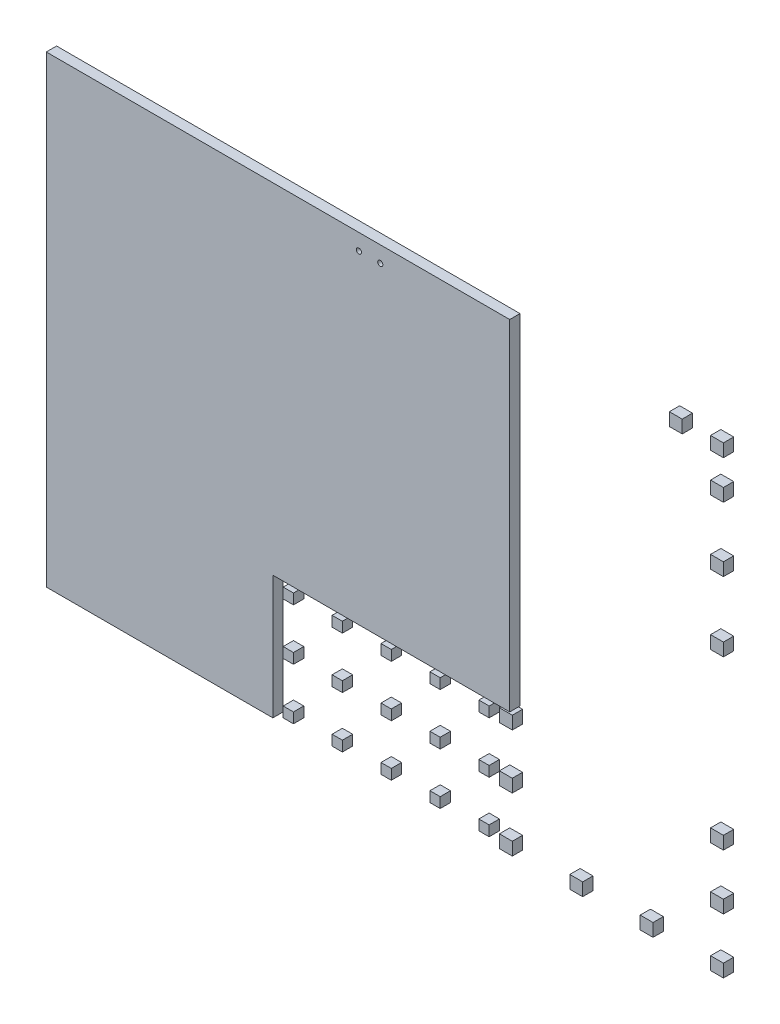
SolidWorks part; units mm, degrees
ref_plane "Спереди" through (0, 0, 0) normal (0, 0, 1) x (1, 0, 0)
ref_plane "Сверху" through (0, 0, 0) normal (0, 1, 0) x (1, 0, 0)
ref_plane "Справа" through (0, 0, 0) normal (1, 0, 0) x (0, 0, -1)
sketch "Эскиз1" plane through (0, 0, 0) normal (0, 0, 1) x (1, 0, 0)
  line L0 (0, 0) -> (9000, 0)
  line L1 (9000, 0) -> (9000, -6600)
  line L2 (9000, -6600) -> (4400, -6600)
  line L3 (4400, -6600) -> (4400, -9000)
  line L4 (4400, -9000) -> (0, -9000)
  line L5 (0, -9000) -> (0, 0)
  line L6 (8800, -4500) -> (8800, -9000) construction
  line L7 (8800, -9000) -> (9050, -9000)
  line L8 (8800, -9000) -> (8800, -8750)
  line L9 (8800, -8750) -> (9050, -8750)
  line L14 (9050, -9000) -> (9050, -8750)
  line L15 (9000, -203) -> (9000, -6400) construction
  line L16 (8797, -6600) -> (4400, -6600) construction
  line L17 (4400, -8797) -> (4400, -6603) construction
  line L18 (203, -9000) -> (4200, -9000) construction
  line L19 (8800, -6630) -> (9050, -6630)
  line L20 (8800, -6630) -> (8800, -6880)
  line L21 (8800, -6880) -> (9050, -6880)
  line L22 (9050, -6630) -> (9050, -6880)
  line L23 (9050, -6880) -> (9050, -7690) construction
  line L24 (8800, -7690) -> (9050, -7690)
  line L25 (8800, -7690) -> (8800, -7940)
  line L26 (8800, -7940) -> (9050, -7940)
  line L27 (9050, -7690) -> (9050, -7940)
  line L28 (9050, -7940) -> (9050, -8750) construction
  line L29 (13150, -9000) -> (0, -9000) construction
  line L30 (10166.6667, -8750) -> (10416.6667, -8750)
  line L31 (10166.6667, -8750) -> (10166.6667, -9000)
  line L32 (10166.6667, -9000) -> (10416.6667, -9000)
  line L33 (10416.6667, -8750) -> (10416.6667, -9000)
  line L34 (9050, -8750) -> (10166.6667, -8750) construction
  line L35 (11533.3333, -8750) -> (11783.3333, -8750)
  line L36 (11533.3333, -8750) -> (11533.3333, -9000)
  line L37 (11533.3333, -9000) -> (11783.3333, -9000)
  line L38 (11783.3333, -8750) -> (11783.3333, -9000)
  line L43 (12900, -8750) -> (13150, -8750)
  line L44 (12900, -8750) -> (12900, -9000)
  line L45 (12900, -9000) -> (13150, -9000)
  line L46 (13150, -8750) -> (13150, -9000)
  line L47 (10416.6667, -8750) -> (11533.3333, -8750) construction
  line L48 (11783.3333, -8750) -> (12900, -8750) construction
  line L49 (13150, -4500) -> (13150, -9000) construction
  line L50 (13150, -6600) -> (12900, -6600)
  line L51 (13150, -6600) -> (13150, -6850)
  line L52 (13150, -6850) -> (12900, -6850)
  line L53 (12900, -6600) -> (12900, -6850)
  line L54 (13150, -7675) -> (12900, -7675)
  line L55 (13150, -7675) -> (13150, -7925)
  line L56 (13150, -7925) -> (12900, -7925)
  line L57 (12900, -7675) -> (12900, -7925)
  line L58 (12900, -7675) -> (12900, -6850) construction
  line L59 (13150, -3600) -> (12900, -3600)
  line L60 (13150, -3600) -> (13150, -3350)
  line L61 (13150, -3350) -> (12900, -3350)
  line L62 (12900, -3600) -> (12900, -3350)
  line L63 (13150, -2000) -> (12900, -2000)
  line L64 (13150, -2000) -> (13150, -2250)
  line L65 (13150, -2250) -> (12900, -2250)
  line L66 (12900, -2000) -> (12900, -2250)
  line L67 (13150, -1000) -> (12900, -1000)
  line L68 (13150, -1000) -> (13150, -750)
  line L69 (13150, -750) -> (12900, -750)
  line L70 (12900, -1000) -> (12900, -750)
  line L71 (13150, 0) -> (12900, 0)
  line L72 (13150, 0) -> (13150, -250)
  line L73 (13150, -250) -> (12900, -250)
  line L74 (12900, 0) -> (12900, -250)
  line L75 (12100, 0) -> (12350, 0)
  line L76 (12100, 0) -> (12100, -250)
  line L77 (12100, -250) -> (12350, -250)
  line L78 (12350, 0) -> (12350, -250)
  line L79 (12900, -7925) -> (12900, -8750) construction
  line L80 (4800, -6900) -> (4800, -7700) construction
  line L81 (4600, -6700) -> (4800, -6700)
  line L82 (4600, -6700) -> (4600, -6900)
  line L83 (4600, -6900) -> (4800, -6900)
  line L84 (4800, -6700) -> (4800, -6900)
  line L85 (4600, -7700) -> (4800, -7700)
  line L86 (4600, -7700) -> (4600, -7900)
  line L87 (4600, -7900) -> (4800, -7900)
  line L88 (4800, -7700) -> (4800, -7900)
  line L89 (4600, -8700) -> (4800, -8700)
  line L90 (4600, -8700) -> (4600, -8900)
  line L91 (4600, -8900) -> (4800, -8900)
  line L92 (4800, -8700) -> (4800, -8900)
  line L93 (4800, -7900) -> (4800, -8700) construction
  line L94 (5550, -6700) -> (5550, -6900)
  line L95 (5550, -6700) -> (5750, -6700)
  line L96 (5750, -6700) -> (5750, -6900)
  line L97 (5550, -6900) -> (5750, -6900)
  line L98 (5550, -7700) -> (5550, -7900)
  line L99 (5550, -7700) -> (5750, -7700)
  line L100 (5750, -7700) -> (5750, -7900)
  line L101 (5550, -7900) -> (5750, -7900)
  line L102 (5550, -8700) -> (5550, -8900)
  line L103 (5550, -8700) -> (5750, -8700)
  line L104 (5750, -8700) -> (5750, -8900)
  line L105 (5550, -8900) -> (5750, -8900)
  line L106 (6500, -6700) -> (6500, -6900)
  line L107 (6500, -6700) -> (6700, -6700)
  line L108 (6700, -6700) -> (6700, -6900)
  line L109 (6500, -6900) -> (6700, -6900)
  line L110 (6500, -7700) -> (6500, -7900)
  line L111 (6500, -7700) -> (6700, -7700)
  line L112 (6700, -7700) -> (6700, -7900)
  line L113 (6500, -7900) -> (6700, -7900)
  line L114 (6500, -8700) -> (6500, -8900)
  line L115 (6500, -8700) -> (6700, -8700)
  line L116 (6700, -8700) -> (6700, -8900)
  line L117 (6500, -8900) -> (6700, -8900)
  line L118 (7450, -6700) -> (7450, -6900)
  line L119 (7450, -6700) -> (7650, -6700)
  line L120 (7650, -6700) -> (7650, -6900)
  line L121 (7450, -6900) -> (7650, -6900)
  line L122 (7450, -7700) -> (7450, -7900)
  line L123 (7450, -7700) -> (7650, -7700)
  line L124 (7650, -7700) -> (7650, -7900)
  line L125 (7450, -7900) -> (7650, -7900)
  line L126 (7450, -8700) -> (7450, -8900)
  line L127 (7450, -8700) -> (7650, -8700)
  line L128 (7650, -8700) -> (7650, -8900)
  line L129 (7450, -8900) -> (7650, -8900)
  line L130 (8400, -6700) -> (8400, -6900)
  line L131 (8400, -6700) -> (8600, -6700)
  line L132 (8600, -6700) -> (8600, -6900)
  line L133 (8400, -6900) -> (8600, -6900)
  line L134 (8400, -7700) -> (8400, -7900)
  line L135 (8400, -7700) -> (8600, -7700)
  line L136 (8600, -7700) -> (8600, -7900)
  line L137 (8400, -7900) -> (8600, -7900)
  line L138 (8400, -8700) -> (8400, -8900)
  line L139 (8400, -8700) -> (8600, -8700)
  line L140 (8600, -8700) -> (8600, -8900)
  line L141 (8400, -8900) -> (8600, -8900)
  circle A0 centre (6486.2448, -312.4922) radius 50
  circle A1 centre (6070.9439, -312.4922) radius 50
  dimension "D3" = 100
  dimension "D1" = 250
  dimension "D2" = 30
  dimension "D4" = 810
  dimension "D5" = 1116.6667
  dimension "D6" = 200
  dimension "D7" = 100
  dimension "D8" = 100
  dimension "D9" = 200
  dimension "D11" = 950
  dimension "D10" = 5
extrude "Бобышка-Вытянуть1" add sketch "Эскиз1" against normal blind 200
